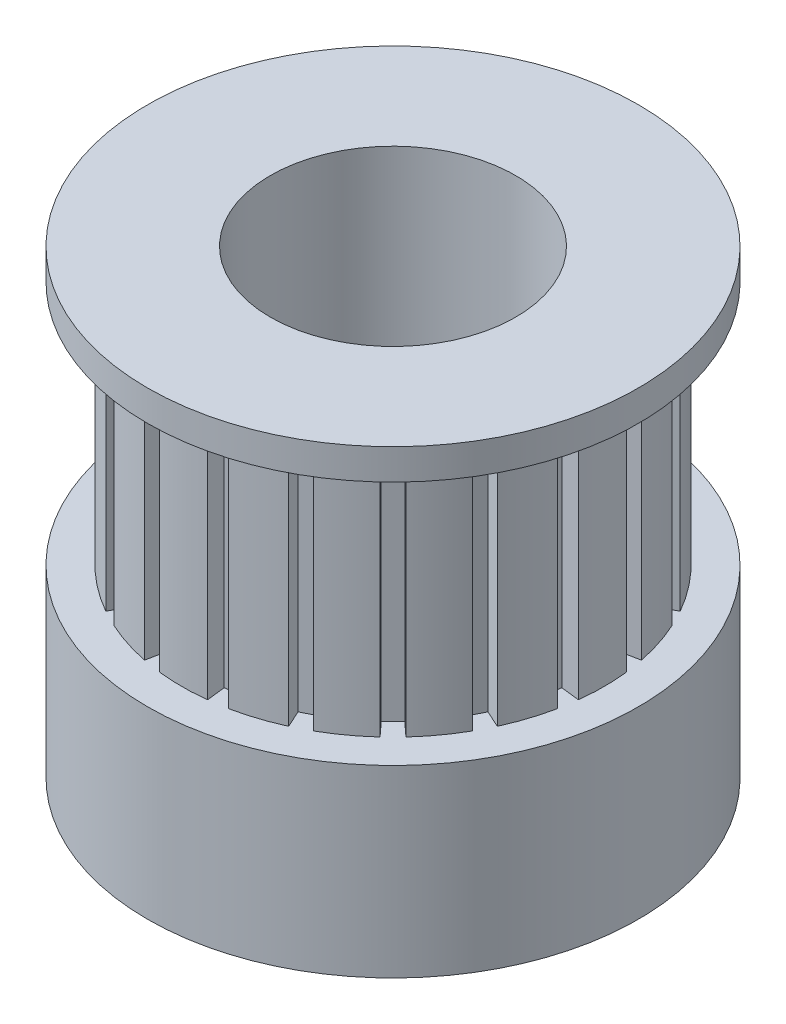
SolidWorks part; units mm, degrees
ref_plane "前视基准面" through (0, 0, 0) normal (0, 0, 1) x (1, 0, 0)
ref_plane "上视基准面" through (0, 0, 0) normal (0, 1, 0) x (1, 0, 0)
ref_plane "右视基准面" through (0, 0, 0) normal (1, 0, 0) x (0, 0, -1)
sketch "草图1" plane through (0, 0, 0) normal (0, 1, 0) x (1, 0, 0)
  circle A0 centre (0, 0) radius 8
  dimension "D1" = 16
extrude "凸台-拉伸1" add sketch "草图1" along normal blind 6
sketch "草图2" plane through (0, 6, 0) normal (0, 1, 0) x (1, 0, 0)
  circle A0 centre (0, 0) radius 6.8702
extrude "凸台-拉伸2" add sketch "草图2" along normal blind 8
sketch "草图3" plane through (0, 14, 0) normal (0, 1, 0) x (1, 0, 0)
  line L0 (-0.7096, 6.2149) -> (-0.7747, 6.7856)
  line L24 (1.2457, 6.13) -> (1.36, 6.6929)
  line L25 (-1.36, 6.6929) -> (-1.3681, 6.7326)
  line L26 (-0.7747, 6.7856) -> (-0.7793, 6.8258)
  line L27 (0.7747, 6.7856) -> (0.7793, 6.8258)
  line L28 (1.36, 6.6929) -> (1.3681, 6.7326)
  line L29 (-1.2457, 6.13) -> (-1.36, 6.6929)
  line L30 (-1.2457, 6.13) -> (-0.9776, 6.1725)
  line L31 (-0.9776, 6.1725) -> (-0.7096, 6.2149)
  line L32 (0.7096, 6.2149) -> (0.7747, 6.7856)
  line L33 (0.7096, 6.2149) -> (0.9776, 6.1725)
  line L34 (0.9776, 6.1725) -> (1.2457, 6.13)
  line L35 (3.079, 5.445) -> (3.3617, 5.945)
  line L36 (2.8337, 6.2141) -> (2.8505, 6.2509)
  line L37 (3.3617, 5.945) -> (3.3816, 5.9803)
  line L38 (2.5954, 5.6915) -> (2.8337, 6.2141)
  line L39 (2.5954, 5.6915) -> (2.8372, 5.5683)
  line L40 (2.8372, 5.5683) -> (3.079, 5.445)
  line L41 (4.6109, 4.2271) -> (5.0343, 4.6152)
  line L42 (4.6152, 5.0343) -> (4.6426, 5.0641)
  line L43 (5.0343, 4.6152) -> (5.0641, 4.6426)
  line L44 (4.2271, 4.6109) -> (4.6152, 5.0343)
  line L45 (4.2271, 4.6109) -> (4.419, 4.419)
  line L46 (4.419, 4.419) -> (4.6109, 4.2271)
  line L47 (5.6915, 2.5954) -> (6.2141, 2.8337)
  line L48 (5.945, 3.3617) -> (5.9803, 3.3816)
  line L49 (6.2141, 2.8337) -> (6.2509, 2.8505)
  line L50 (5.445, 3.079) -> (5.945, 3.3617)
  line L51 (5.445, 3.079) -> (5.5683, 2.8372)
  line L52 (5.5683, 2.8372) -> (5.6915, 2.5954)
  line L53 (6.2149, 0.7096) -> (6.7856, 0.7747)
  line L54 (6.6929, 1.36) -> (6.7326, 1.3681)
  line L55 (6.7856, 0.7747) -> (6.8258, 0.7793)
  line L56 (6.13, 1.2457) -> (6.6929, 1.36)
  line L57 (6.13, 1.2457) -> (6.1725, 0.9776)
  line L58 (6.1725, 0.9776) -> (6.2149, 0.7096)
  line L59 (6.13, -1.2457) -> (6.6929, -1.36)
  line L60 (6.7856, -0.7747) -> (6.8258, -0.7793)
  line L61 (6.6929, -1.36) -> (6.7326, -1.3681)
  line L62 (6.2149, -0.7096) -> (6.7856, -0.7747)
  line L63 (6.2149, -0.7096) -> (6.1725, -0.9776)
  line L64 (6.1725, -0.9776) -> (6.13, -1.2457)
  line L65 (5.445, -3.079) -> (5.945, -3.3617)
  line L66 (6.2141, -2.8337) -> (6.2509, -2.8505)
  line L67 (5.945, -3.3617) -> (5.9803, -3.3816)
  line L68 (5.6915, -2.5954) -> (6.2141, -2.8337)
  line L69 (5.6915, -2.5954) -> (5.5683, -2.8372)
  line L70 (5.5683, -2.8372) -> (5.445, -3.079)
  line L71 (4.2271, -4.6109) -> (4.6152, -5.0343)
  line L72 (5.0343, -4.6152) -> (5.0641, -4.6426)
  line L73 (4.6152, -5.0343) -> (4.6426, -5.0641)
  line L74 (4.6109, -4.2271) -> (5.0343, -4.6152)
  line L75 (4.6109, -4.2271) -> (4.419, -4.419)
  line L76 (4.419, -4.419) -> (4.2271, -4.6109)
  line L77 (2.5954, -5.6915) -> (2.8337, -6.2141)
  line L78 (3.3617, -5.945) -> (3.3816, -5.9803)
  line L79 (2.8337, -6.2141) -> (2.8505, -6.2509)
  line L80 (3.079, -5.445) -> (3.3617, -5.945)
  line L81 (3.079, -5.445) -> (2.8372, -5.5683)
  line L82 (2.8372, -5.5683) -> (2.5954, -5.6915)
  line L83 (0.7096, -6.2149) -> (0.7747, -6.7856)
  line L84 (1.36, -6.6929) -> (1.3681, -6.7326)
  line L85 (0.7747, -6.7856) -> (0.7793, -6.8258)
  line L86 (1.2457, -6.13) -> (1.36, -6.6929)
  line L87 (1.2457, -6.13) -> (0.9776, -6.1725)
  line L88 (0.9776, -6.1725) -> (0.7096, -6.2149)
  line L89 (-1.2457, -6.13) -> (-1.36, -6.6929)
  line L90 (-0.7747, -6.7856) -> (-0.7793, -6.8258)
  line L91 (-1.36, -6.6929) -> (-1.3681, -6.7326)
  line L92 (-0.7096, -6.2149) -> (-0.7747, -6.7856)
  line L93 (-0.7096, -6.2149) -> (-0.9776, -6.1725)
  line L94 (-0.9776, -6.1725) -> (-1.2457, -6.13)
  line L95 (-3.079, -5.445) -> (-3.3617, -5.945)
  line L96 (-2.8337, -6.2141) -> (-2.8505, -6.2509)
  line L97 (-3.3617, -5.945) -> (-3.3816, -5.9803)
  line L98 (-2.5954, -5.6915) -> (-2.8337, -6.2141)
  line L99 (-2.5954, -5.6915) -> (-2.8372, -5.5683)
  line L100 (-2.8372, -5.5683) -> (-3.079, -5.445)
  line L101 (-4.6109, -4.2271) -> (-5.0343, -4.6152)
  line L102 (-4.6152, -5.0343) -> (-4.6426, -5.0641)
  line L103 (-5.0343, -4.6152) -> (-5.0641, -4.6426)
  line L104 (-4.2271, -4.6109) -> (-4.6152, -5.0343)
  line L105 (-4.2271, -4.6109) -> (-4.419, -4.419)
  line L106 (-4.419, -4.419) -> (-4.6109, -4.2271)
  line L107 (-5.6915, -2.5954) -> (-6.2141, -2.8337)
  line L108 (-5.945, -3.3617) -> (-5.9803, -3.3816)
  line L109 (-6.2141, -2.8337) -> (-6.2509, -2.8505)
  line L110 (-5.445, -3.079) -> (-5.945, -3.3617)
  line L111 (-5.445, -3.079) -> (-5.5683, -2.8372)
  line L112 (-5.5683, -2.8372) -> (-5.6915, -2.5954)
  line L113 (-6.2149, -0.7096) -> (-6.7856, -0.7747)
  line L114 (-6.6929, -1.36) -> (-6.7326, -1.3681)
  line L115 (-6.7856, -0.7747) -> (-6.8258, -0.7793)
  line L116 (-6.13, -1.2457) -> (-6.6929, -1.36)
  line L117 (-6.13, -1.2457) -> (-6.1725, -0.9776)
  line L118 (-6.1725, -0.9776) -> (-6.2149, -0.7096)
  line L119 (-6.13, 1.2457) -> (-6.6929, 1.36)
  line L120 (-6.7856, 0.7747) -> (-6.8258, 0.7793)
  line L121 (-6.6929, 1.36) -> (-6.7326, 1.3681)
  line L122 (-6.2149, 0.7096) -> (-6.7856, 0.7747)
  line L123 (-6.2149, 0.7096) -> (-6.1725, 0.9776)
  line L124 (-6.1725, 0.9776) -> (-6.13, 1.2457)
  line L125 (-5.445, 3.079) -> (-5.945, 3.3617)
  line L126 (-6.2141, 2.8337) -> (-6.2509, 2.8505)
  line L127 (-5.945, 3.3617) -> (-5.9803, 3.3816)
  line L128 (-5.6915, 2.5954) -> (-6.2141, 2.8337)
  line L129 (-5.6915, 2.5954) -> (-5.5683, 2.8372)
  line L130 (-5.5683, 2.8372) -> (-5.445, 3.079)
  line L131 (-4.2271, 4.6109) -> (-4.6152, 5.0343)
  line L132 (-5.0343, 4.6152) -> (-5.0641, 4.6426)
  line L133 (-4.6152, 5.0343) -> (-4.6426, 5.0641)
  line L134 (-4.6109, 4.2271) -> (-5.0343, 4.6152)
  line L135 (-4.6109, 4.2271) -> (-4.419, 4.419)
  line L136 (-4.419, 4.419) -> (-4.2271, 4.6109)
  line L137 (-2.5954, 5.6915) -> (-2.8337, 6.2141)
  line L138 (-3.3617, 5.945) -> (-3.3816, 5.9803)
  line L139 (-2.8337, 6.2141) -> (-2.8505, 6.2509)
  line L140 (-3.079, 5.445) -> (-3.3617, 5.945)
  line L141 (-3.079, 5.445) -> (-2.8372, 5.5683)
  line L142 (-2.8372, 5.5683) -> (-2.5954, 5.6915)
  arc A0 (-0.7793, 6.8258) -> (-1.3681, 6.7326) centre (0, 0) ccw
  arc A1 (1.3681, 6.7326) -> (0.7793, 6.8258) centre (0, 0) ccw
  arc A2 (3.3816, 5.9803) -> (2.8505, 6.2509) centre (0, 0) ccw
  arc A3 (5.0641, 4.6426) -> (4.6426, 5.0641) centre (0, 0) ccw
  arc A4 (6.2509, 2.8505) -> (5.9803, 3.3816) centre (0, 0) ccw
  arc A5 (6.8258, 0.7793) -> (6.7326, 1.3681) centre (0, 0) ccw
  arc A6 (6.7326, -1.3681) -> (6.8258, -0.7793) centre (0, 0) ccw
  arc A7 (5.9803, -3.3816) -> (6.2509, -2.8505) centre (0, 0) ccw
  arc A8 (4.6426, -5.0641) -> (5.0641, -4.6426) centre (0, 0) ccw
  arc A9 (2.8505, -6.2509) -> (3.3816, -5.9803) centre (0, 0) ccw
  arc A10 (0.7793, -6.8258) -> (1.3681, -6.7326) centre (0, 0) ccw
  arc A11 (-1.3681, -6.7326) -> (-0.7793, -6.8258) centre (0, 0) ccw
  arc A12 (-3.3816, -5.9803) -> (-2.8505, -6.2509) centre (0, 0) ccw
  arc A13 (-5.0641, -4.6426) -> (-4.6426, -5.0641) centre (0, 0) ccw
  arc A14 (-6.2509, -2.8505) -> (-5.9803, -3.3816) centre (0, 0) ccw
  arc A15 (-6.8258, -0.7793) -> (-6.7326, -1.3681) centre (0, 0) ccw
  arc A16 (-6.7326, 1.3681) -> (-6.8258, 0.7793) centre (0, 0) ccw
  arc A17 (-5.9803, 3.3816) -> (-6.2509, 2.8505) centre (0, 0) ccw
  arc A18 (-4.6426, 5.0641) -> (-5.0641, 4.6426) centre (0, 0) ccw
  arc A19 (-2.8505, 6.2509) -> (-3.3816, 5.9803) centre (0, 0) ccw
  point P144 (0, 0)
  dimension "D1" = 20
extrude "切除-拉伸1" cut sketch "草图3" against normal blind 8
sketch "草图4" plane through (0, 14, 0) normal (0, 1, 0) x (1, 0, 0)
  circle A0 centre (0, 0) radius 8
extrude "凸台-拉伸3" add sketch "草图4" along normal blind 1
sketch "草图5" plane through (0, 15, 0) normal (0, 1, 0) x (1, 0, 0)
  circle A0 centre (0, 0) radius 4
  dimension "D1" = 8
extrude "切除-拉伸2" cut sketch "草图5" against normal through all
